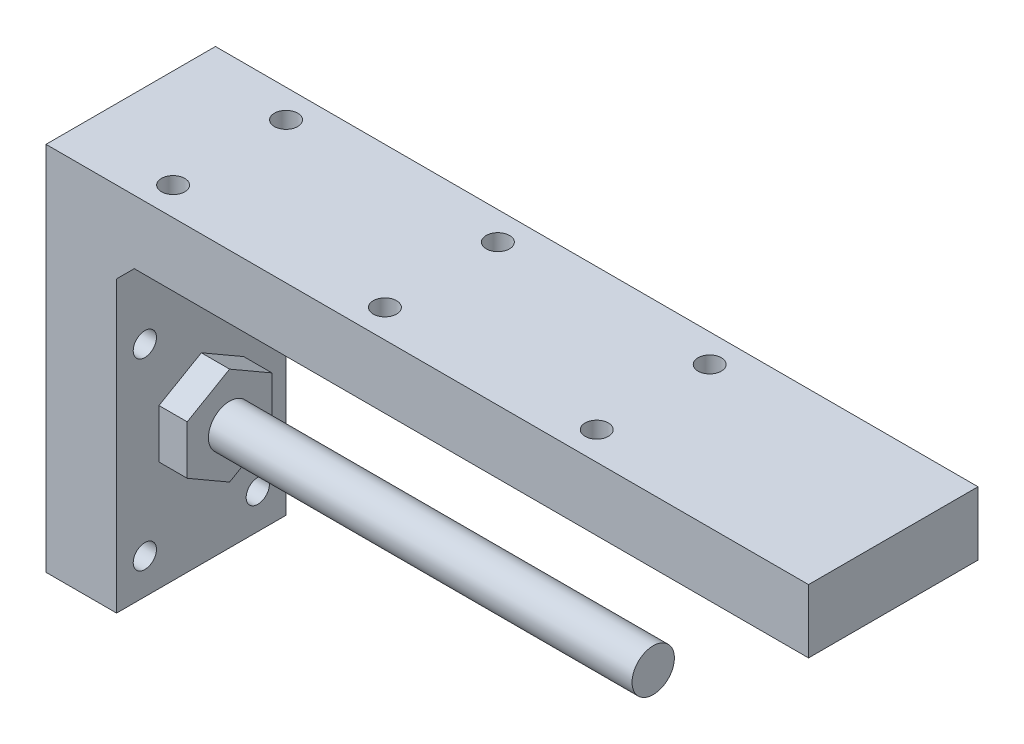
SolidWorks part; units mm, degrees
ref_plane "Front" through (0, 0, 0) normal (0, 0, 1) x (1, 0, 0)
ref_plane "Top" through (0, 0, 0) normal (0, 1, 0) x (1, 0, 0)
ref_plane "Right" through (0, 0, 0) normal (1, 0, 0) x (0, 0, -1)
sketch "Sketch1" plane through (0, 0, 0) normal (0, 0, 1) x (1, 0, 0)
  line L0 (0, 0) -> (0, 52.5)
  line L1 (0, 52.5) -> (108, 52.5)
  line L2 (108, 52.5) -> (108, 43.5)
  line L3 (108, 43.5) -> (10, 43.5)
  line L4 (10, 43.5) -> (10, 0)
  line L5 (10, 0) -> (0, 0)
  dimension "D1" = 108
  dimension "D2" = 9
  dimension "D3" = 10
  dimension "D4" = 52.5
extrude "Boss-Extrude1" add sketch "Sketch1" along normal blind 24
chamfer "Chamfer1" distance 2.5 angle 45 1 edges at (10, 43.5, 12)
sketch "Sketch2" plane through (10, 0, 0) normal (1, 0, 0) x (0, 0, -1)
  line L0 (-12, 19) -> (-12, 0) construction
  line L1 (-6, 22.4641) -> (-12, 25.9282)
  line L2 (-12, 25.9282) -> (-18, 22.4641)
  line L3 (-18, 22.4641) -> (-18, 15.5359)
  line L4 (-18, 15.5359) -> (-12, 12.0718)
  line L5 (-12, 12.0718) -> (-6, 15.5359)
  line L6 (-6, 15.5359) -> (-6, 22.4641)
  line L7 (-24, 0) -> (0, 0) construction
  circle A0 centre (-12, 19) radius 6 construction
  dimension "D2" = 12
  dimension "D1" = 19
extrude "Boss-Extrude2" add sketch "Sketch2" along normal blind 4
sketch "Sketch3" plane through (14, 0, 0) normal (1, 0, 0) x (0, 0, -1)
  line L0 (-12, 25.9282) -> (-12, 12.0718) construction
  circle A0 centre (-12, 19) radius 3
  point P2 (0, 0)
  dimension "D1" = 6
extrude "Boss-Extrude3" add sketch "Sketch3" along normal blind 60
hole_wizard "M4x0.7 Tapped Hole1" positions "Sketch4" profile "Sketch5" tap size "M4x0.7" standard "ANSI Metric"
sketch "Sketch4" plane through (0, 52.5, 0) normal (0, 1, 0) x (1, 0, 0)
  line L0 (0, -24) -> (0, 0) construction
  line L1 (14, -4) -> (14, -20) construction
  line L3 (44, -4) -> (44, -20) construction
  line L5 (74, -4) -> (74, -20) construction
  line L7 (74, -12) -> (0, -12) construction
  point P0 (14, -4)
  point P2 (44, -4)
  point P4 (74, -4)
  point P6 (74, -20)
  point P8 (44, -20)
  point P10 (14, -20)
  point P31 (14, -12)
  point P32 (44, -12)
  dimension "D1" = 16
  dimension "D2" = 30
  dimension "D3" = 30
  dimension "D4" = 14
sketch "Sketch5" plane through (14, 52.5, 4) normal (1, 0, 0) x (0, 0, 1)
  line L0 (0, 0) -> (0, 11.0914)
  line L1 (0, 11.0914) -> (1.65, 10.1)
  line L2 (1.65, 10.1) -> (1.65, 0)
  line L5 (1.65, 0) -> (0, 0)
  line L10 (0, 11.0914) -> (-1.65, 10.1) construction
  line L11 (0, -6.35) -> (0, 107.95) construction
  dimension "Tap Drill Dia." = 3.3
  dimension "Tap Drill Depth" = 10.1
  dimension "Drill Angle" = 118
cosmetic thread "Hole Thread1" parameters "D1"=8, "D2"=4
cosmetic thread "Hole Thread2" parameters "D1"=8, "D2"=4
cosmetic thread "Hole Thread3" parameters "D1"=8, "D2"=4
cosmetic thread "Hole Thread4" parameters "D1"=8, "D2"=4
cosmetic thread "Hole Thread5" parameters "D1"=8, "D2"=4
cosmetic thread "Hole Thread6" parameters "D1"=8, "D2"=4
hole_wizard "M4x0.7 Tapped Hole2" positions "Sketch6" profile "Sketch7" tap size "M4x0.7" standard "ANSI Metric"
sketch "Sketch6" plane through (0, 0, 0) normal (-1, 0, 0) x (0, 0, 1)
  line L0 (24, 52.5) -> (0, 52.5) construction
  line L2 (4, 5) -> (20, 5) construction
  line L4 (12, 5) -> (12, 0) construction
  line L5 (24, 0) -> (0, 0) construction
  point P0 (4, 31)
  point P2 (20, 31)
  point P4 (20, 5)
  point P6 (4, 5)
  dimension "D1" = 16
  dimension "D2" = 21.5
  dimension "D3" = 26
sketch "Sketch7" plane through (0, 31, 4) normal (0, 1, 0) x (0, 0, 1)
  line L0 (0, 0) -> (0, 11.0914)
  line L1 (0, 11.0914) -> (1.65, 10.1)
  line L2 (1.65, 10.1) -> (1.65, 0)
  line L5 (1.65, 0) -> (0, 0)
  line L10 (0, 11.0914) -> (-1.65, 10.1) construction
  line L11 (0, -6.35) -> (0, 107.95) construction
  dimension "Tap Drill Dia." = 3.3
  dimension "Tap Drill Depth" = 10.1
  dimension "Drill Angle" = 118
cosmetic thread "Hole Thread7" parameters "D1"=8, "D2"=4
cosmetic thread "Hole Thread8" parameters "D1"=8, "D2"=4
cosmetic thread "Hole Thread9" parameters "D1"=8, "D2"=4
cosmetic thread "Hole Thread10" parameters "D1"=8, "D2"=4
